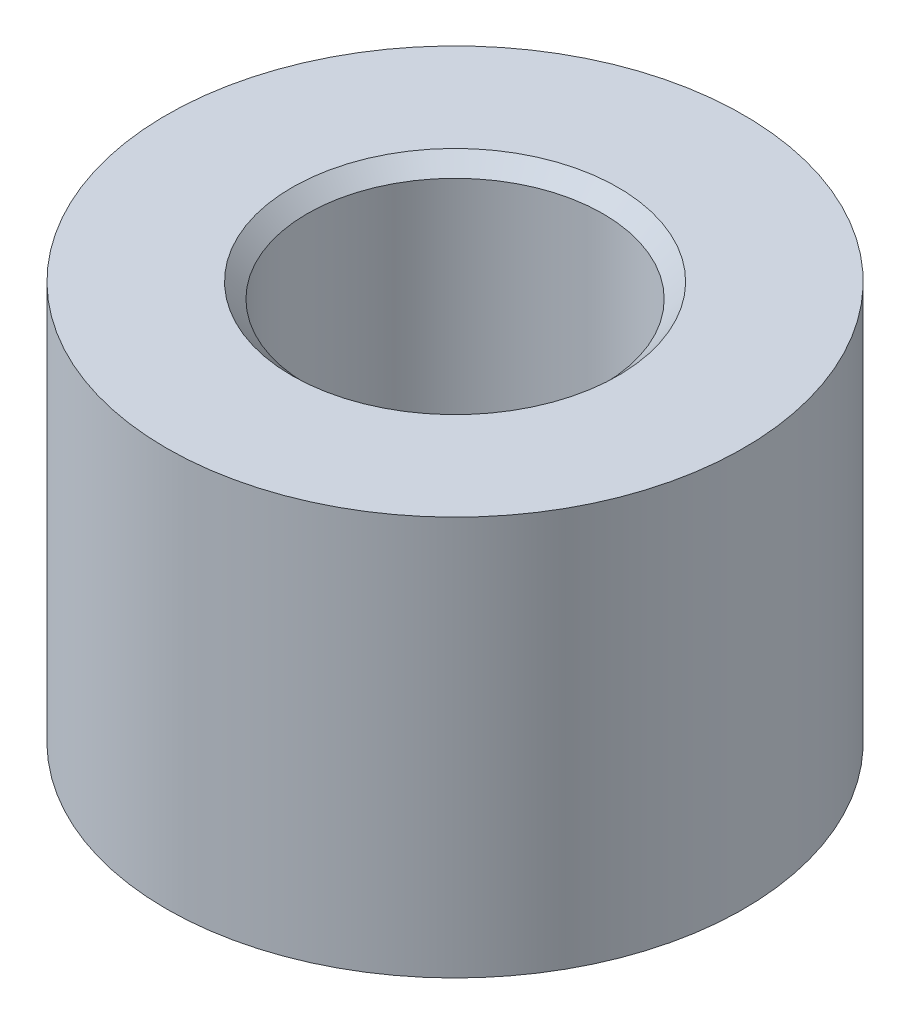
SolidWorks part; units mm, degrees
ref_plane "Front Plane" through (0, 0, 0) normal (0, 0, 1) x (1, 0, 0)
ref_plane "Top Plane" through (0, 0, 0) normal (0, 1, 0) x (1, 0, 0)
ref_plane "Right Plane" through (0, 0, 0) normal (1, 0, 0) x (0, 0, -1)
sketch "Sketch1" plane through (0, 0, 0) normal (0, 1, 0) x (1, 0, 0)
  circle A0 centre (0, 0) radius 1.9526
  circle A1 centre (0, 0) radius 3.81
  dimension "D1" = 3.9052
  dimension "D2" = 7.62
extrude "Boss-Extrude1" add sketch "Sketch1" along normal blind 5.269
chamfer "Chamfer1" distance 0.2 angle 45 2 edges at (0, 0, 1.9526) (0, 5.269, 1.9526)
